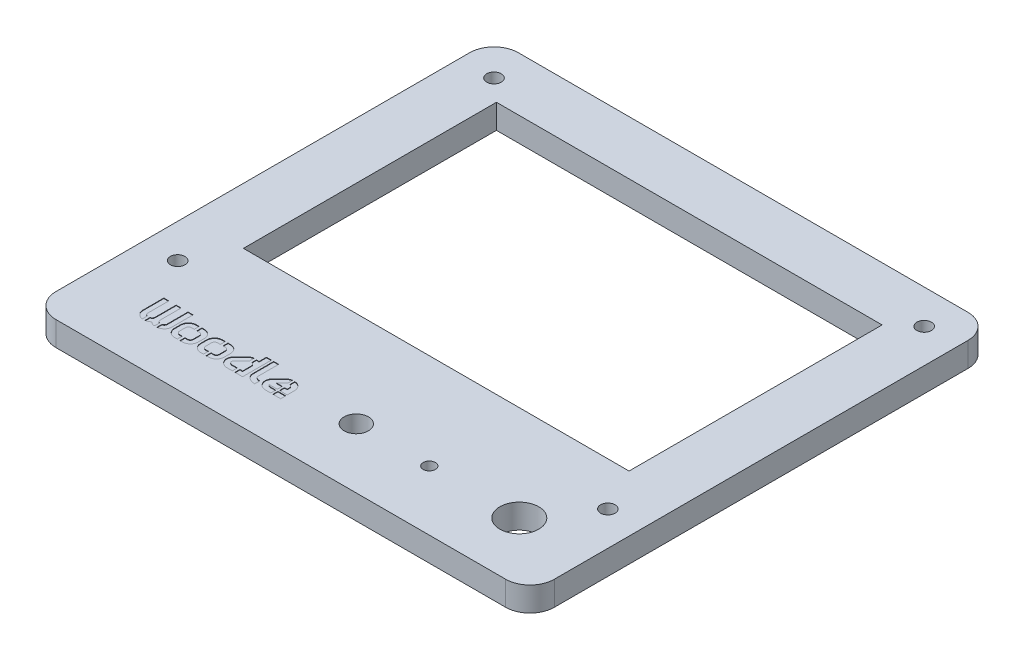
SolidWorks part; units mm, degrees
material "Maple"
ref_plane "Front Plane" through (0, 0, 0) normal (0, 0, 1) x (1, 0, 0)
ref_plane "Top Plane" through (0, 0, 0) normal (0, 1, 0) x (1, 0, 0)
ref_plane "Right Plane" through (0, 0, 0) normal (1, 0, 0) x (0, 0, -1)
sketch "Sketch1" plane through (0, 0, 0) normal (0, 1, 0) x (1, 0, 0)
  line L0 (-39.125, -25.5) -> (39.125, 25.5) construction
  line L1 (-39.125, 25.5) -> (39.125, 25.5) construction
  line L2 (-39.125, 25.5) -> (-39.125, -25.5) construction
  line L3 (-39.125, -25.5) -> (39.125, -25.5) construction
  line L4 (39.125, 25.5) -> (39.125, -25.5) construction
  line L5 (-51.2, 37.07) -> (51.2, 37.07)
  line L6 (-51.2, 37.07) -> (-51.2, -57.93)
  line L7 (-51.2, -57.93) -> (51.2, -57.93)
  line L8 (51.2, 37.07) -> (51.2, -57.93)
  line L9 (-39.625, 26) -> (39.625, 26)
  line L10 (39.625, 26) -> (39.625, -26)
  line L11 (-39.625, -26) -> (39.625, -26)
  line L12 (-39.625, 26) -> (-39.625, -26)
  line L13 (0, 0) -> (0, 30.07) construction
  line L14 (-44.2, 30.07) -> (44.2, 30.07) construction
  line L15 (-44.2, 30.07) -> (-44.2, -34.93) construction
  line L16 (-44.2, -34.93) -> (44.2, -34.93) construction
  line L17 (44.2, 30.07) -> (44.2, -34.93) construction
  circle A0 centre (36.7, -45.63) radius 4
  circle A1 centre (-44.2, 30.07) radius 1.5
  circle A2 centre (44.2, 30.07) radius 1.5
  circle A3 centre (44.2, -34.93) radius 1.5
  circle A4 centre (-44.2, -34.93) radius 1.5
  circle A5 centre (3.2, -45.63) radius 2.5
  circle A6 centre (18.2, -45.63) radius 1.25
  dimension "D10" = 3
  dimension "D11" = 8
  dimension "D12" = 5
  dimension "D17" = 2.5
  dimension "D1" = 51
  dimension "D2" = 78.25
  dimension "D4" = 88.4
  dimension "D5" = 65
  dimension "D6" = 4.57
  dimension "D7" = 7
  dimension "D8" = 7
  dimension "D9" = 7
  dimension "D13" = 10.7
  dimension "D14" = 7.5
  dimension "D15" = 33.5
  dimension "D16" = 18.5
  dimension "D18" = 95
  dimension "D3" = 0.5
extrude "Boss-Extrude1" add sketch "Sketch1" along normal blind 5
sketch "Sketch3" plane through (0, 5, 0) normal (0, 1, 0) x (1, 0, 0)
  line L1 (-51.2, 37.07) -> (-51.2, -57.93) construction
  line L2 (-51.2, -57.93) -> (51.2, -57.93) construction
  text T0 "Woodle" font "Sylar Stencil" height 6
  dimension "D1" = 9
  dimension "D2" = 12
extrude "Cut-Extrude1" cut sketch "Sketch3" against normal blind 0.1
fillet "Fillet1" radius 5 4 edges at (-51.2, 2.5, -37.07) (51.2, 2.5, -37.07) (51.2, 2.5, 57.93) (-51.2, 2.5, 57.93)
